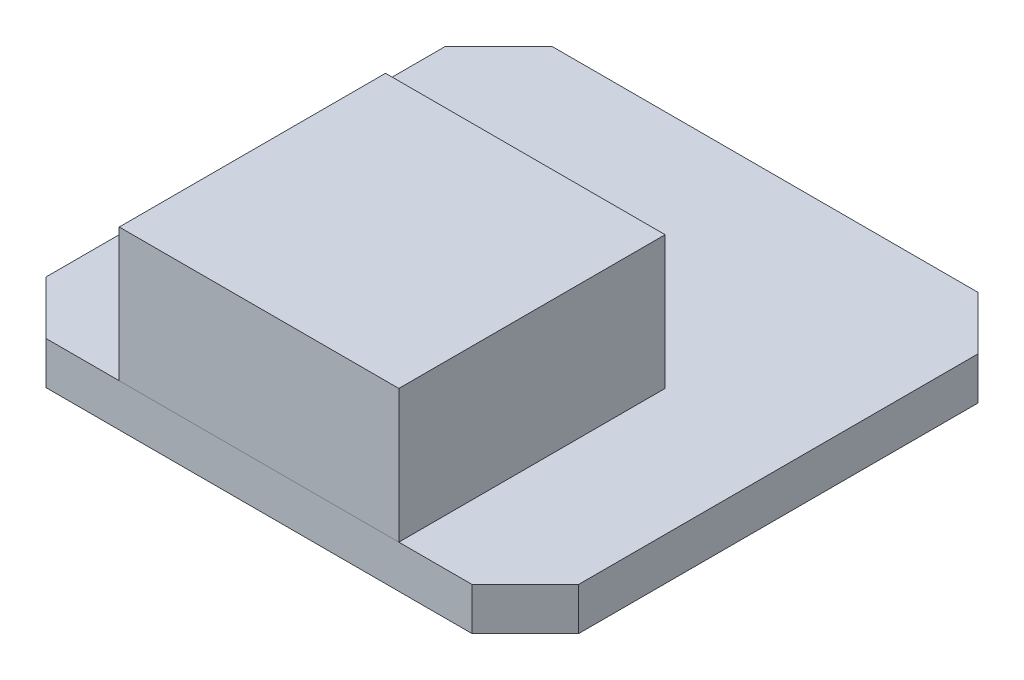
SolidWorks part; units mm, degrees
ref_plane "Front" through (0, 0, 0) normal (0, 0, 1) x (1, 0, 0)
ref_plane "Top" through (0, 0, 0) normal (0, 1, 0) x (1, 0, 0)
ref_plane "Right" through (0, 0, 0) normal (1, 0, 0) x (0, 0, -1)
sketch "Sketch1" plane through (0, 0, 0) normal (0, 1, 0) x (1, 0, 0)
  line L1 (0, 0) -> (20, 0)
  line L2 (0, 0) -> (0, 19)
  line L3 (0, 19) -> (20, 19)
  line L4 (20, 0) -> (20, 19)
  dimension "D1" = 20
  dimension "D2" = 19
extrude "Boss-Extrude1" add sketch "Sketch1" along normal blind 1.6
chamfer "Chamfer1" distance 2 angle 45 4 edges at (0, 0.8, -19) (20, 0.8, -19) (0, 0.8, 0) (20, 0.8, 0)
sketch "Sketch2" plane through (0, 1.6, 0) normal (0, 1, 0) x (1, 0, 0)
  line L0 (2, 0) -> (18, 0) construction
  line L1 (4.75, 0) -> (15.25, 0)
  line L2 (4.75, 0) -> (4.75, 10)
  line L3 (4.75, 10) -> (15.25, 10)
  line L4 (15.25, 0) -> (15.25, 10)
  point P6 (10, 0)
  point P7 (10, 0)
  dimension "D1" = 10.5
  dimension "D2" = 10
extrude "Boss-Extrude2" add sketch "Sketch2" along normal blind 5 separate body
